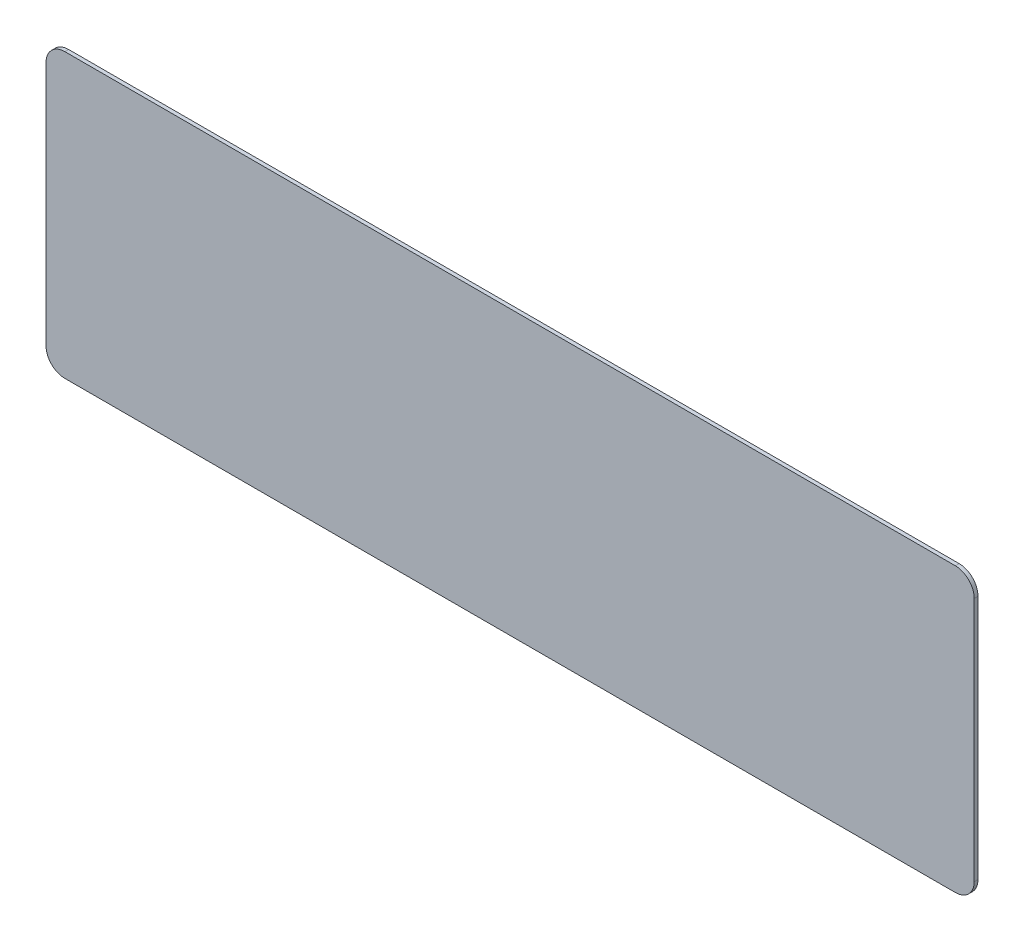
SolidWorks part; units mm, degrees
ref_plane "Front Plane" through (0, 0, 0) normal (0, 0, 1) x (1, 0, 0)
ref_plane "Top Plane" through (0, 0, 0) normal (0, 1, 0) x (1, 0, 0)
ref_plane "Right Plane" through (0, 0, 0) normal (1, 0, 0) x (0, 0, -1)
sketch "Sketch1" plane through (0, 0, 0) normal (0, 0, 1) x (1, 0, 0)
  line L0 (-123, -367) -> (-123, -217)
  line L5 (-123, -217) -> (369, -217)
  line L6 (369, -367) -> (369, -217)
  line L7 (-123, -367) -> (369, -367)
  dimension "D1" = 150
  dimension "D2" = 492
extrude "Boss-Extrude1" add sketch "Sketch1" along normal blind 2 contours L0 L5 L6 L7
fillet "Fillet1" radius 10 4 edges at (-123, -367, 1) (369, -367, 1) (369, -217, 1) (-123, -217, 1)
ref_plane "Plane1" through (0, -292, 0) normal (0, 1, 0) x (1, 0, 0)
extrude "Cut-Extrude2" cut sketch "Sketch3" against normal blind 600
sketch "Sketch3" plane through (-898.4713, 35.1656, 504) normal (0, 0, 1) x (0, 1, 0)
  line L1 (-764.1656, -1134.4713) -> (-484.1656, -1134.4713)
  line L2 (-764.1656, -1134.4713) -> (-764.1656, -662.4713)
  line L3 (-764.1656, -662.4713) -> (-484.1656, -662.4713)
  line L4 (-484.1656, -1134.4713) -> (-484.1656, -662.4713)
  line L5 (-764.1656, -1134.4713) -> (-484.1656, -662.4713) construction
  line L6 (-764.1656, -662.4713) -> (-484.1656, -1134.4713) construction
  line L10 (-189.1656, -662.4713) -> (-79.1656, -662.4713)
  line L11 (-199.1656, -672.4713) -> (-199.1656, -1124.4713)
  line L12 (-189.1656, -1134.4713) -> (-79.1656, -1134.4713)
  line L13 (-69.1656, -672.4713) -> (-69.1656, -1124.4713)
  arc A0 (-79.1656, -662.4713) -> (-69.1656, -672.4713) centre (-79.1656, -672.4713) cw
  arc A1 (-189.1656, -662.4713) -> (-199.1656, -672.4713) centre (-189.1656, -672.4713) ccw
  arc A2 (-79.1656, -1134.4713) -> (-69.1656, -1124.4713) centre (-79.1656, -1124.4713) ccw
  arc A3 (-199.1656, -1124.4713) -> (-189.1656, -1134.4713) centre (-189.1656, -1124.4713) ccw
  point P0 (-624.1656, -898.4713)
  point P21 (-69.1656, -662.4713)
  point P24 (-199.1656, -662.4713)
  point P27 (-69.1656, -1134.4713)
ref_plane "Plane2" through (123, 0, 0) normal (-1, 0, 0) x (0, 0, 1)
ref_plane "Plane3" through (123, 0, 0) normal (-1, 0, 0) x (0, 0, 1)
